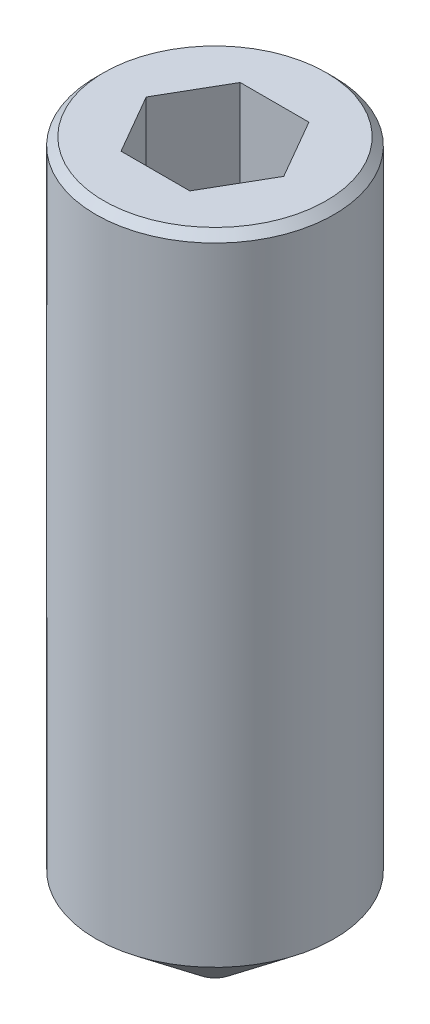
SolidWorks part; units mm, degrees
ref_plane "前视基准面" through (0, 0, 0) normal (0, 0, 1) x (1, 0, 0)
ref_plane "上视基准面" through (0, 0, 0) normal (0, 1, 0) x (1, 0, 0)
ref_plane "右视基准面" through (0, 0, 0) normal (1, 0, 0) x (0, 0, -1)
sketch "草图1" plane through (0, 0, 0) normal (0, 0, 1) x (1, 0, 0)
  line L0 (0, 0) -> (1.5, 0)
  line L1 (1.5, 0) -> (1.5, -8)
  line L2 (1.5, -8) -> (0.25, -9)
  line L3 (0, -9) -> (0, 0)
  line L4 (0, 8.7135) -> (0, -8.7135) construction
  line L5 (0.25, -9) -> (0, -9)
  point P10 (0, 0)
  dimension "D1" = 3
  dimension "D2" = 8
  dimension "D3" = 1
  dimension "D4" = 0.5
revolve "旋转1" add sketch "草图1" angle 360 about L4
sketch "草图2" plane through (0, 0, 0) normal (0, 1, 0) x (1, 0, 0)
  line L1 (-0.433, -0.75) -> (0.433, -0.75)
  line L2 (0.433, -0.75) -> (0.866, 0)
  line L3 (0.866, 0) -> (0.433, 0.75)
  line L4 (0.433, 0.75) -> (-0.433, 0.75)
  line L5 (-0.433, 0.75) -> (-0.866, 0)
  line L6 (-0.866, 0) -> (-0.433, -0.75)
  circle A0 centre (0, 0) radius 0.75 construction
  dimension "D1" = 1.5
extrude "切除-拉伸1" cut sketch "草图2" against normal blind 1.5
chamfer "倒角1" distance 0.1 angle 45 1 edges at (0, 0, 1.5)
